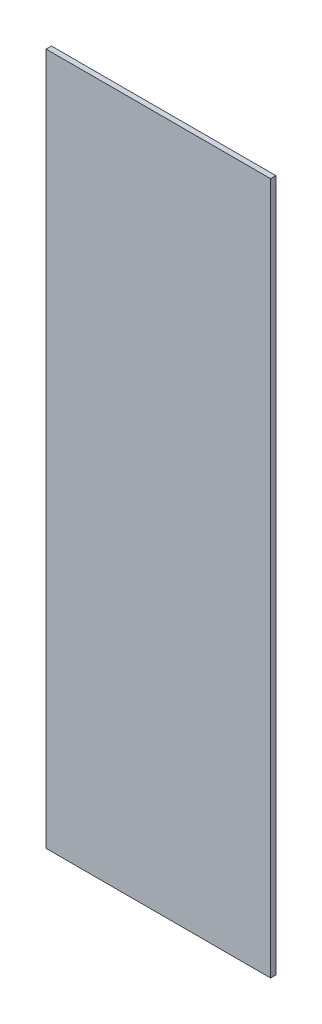
SolidWorks part; units mm, degrees
material "Pine"
ref_plane "Front Plane" through (0, 0, 0) normal (0, 0, 1) x (1, 0, 0)
ref_plane "Top Plane" through (0, 0, 0) normal (0, 1, 0) x (1, 0, 0)
ref_plane "Right Plane" through (0, 0, 0) normal (1, 0, 0) x (0, 0, -1)
sketch "Sketch1" plane through (0, 0, 0) normal (0, 0, 1) x (1, 0, 0)
  line L1 (-267.5, -825) -> (267.5, -825)
  line L2 (-267.5, -825) -> (-267.5, 825)
  line L3 (-267.5, 825) -> (267.5, 825)
  line L4 (267.5, -825) -> (267.5, 825)
  line L5 (-267.5, -825) -> (267.5, 825) construction
  line L6 (-267.5, 825) -> (267.5, -825) construction
  point P0 (0, 0)
  dimension "D1" = 535
  dimension "D2" = 1650
extrude "Boss-Extrude1" add sketch "Sketch1" along normal blind 12.7
